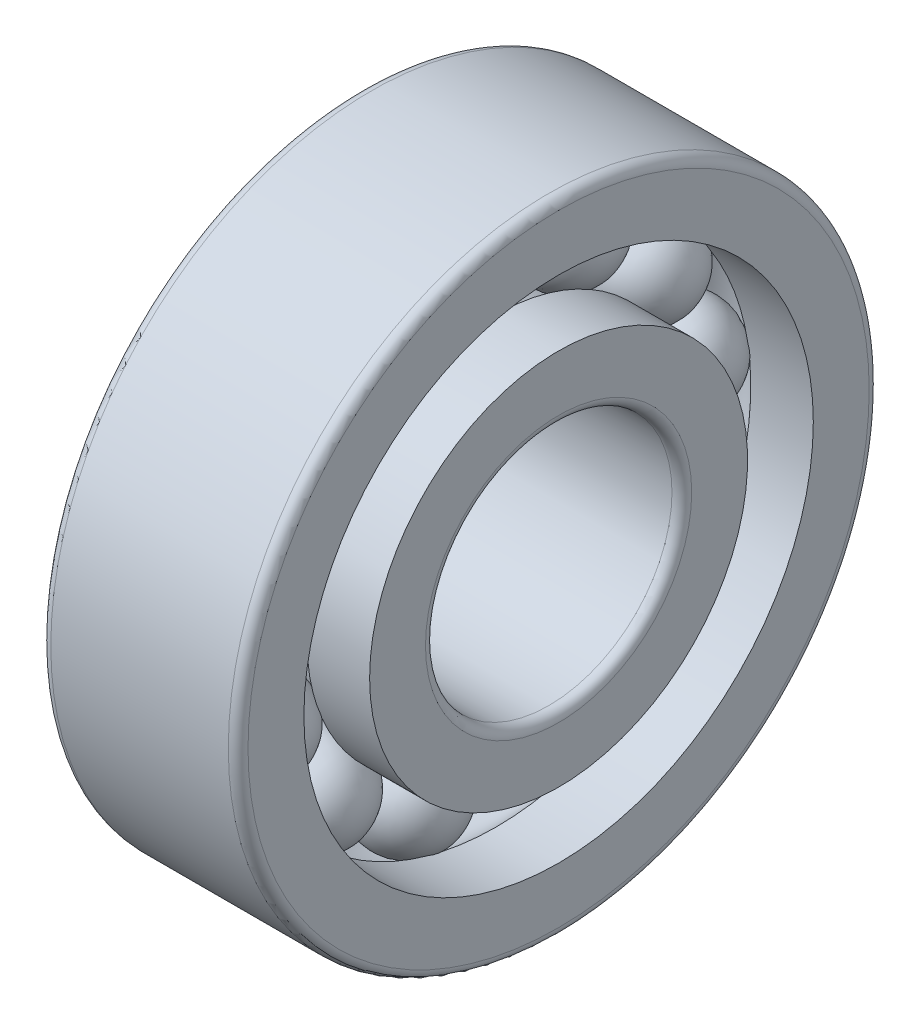
SolidWorks part; units mm, degrees
ref_plane "Front" through (0, 0, 0) normal (0, 0, 1) x (1, 0, 0)
ref_plane "Top" through (0, 0, 0) normal (0, 1, 0) x (1, 0, 0)
ref_plane "Right" through (0, 0, 0) normal (1, 0, 0) x (0, 0, -1)
other "Configuration Table"
sketch "Sketch1" plane through (0, 0, 0) normal (0, 0, 1) x (1, 0, 0)
  line L0 (-9.6833, 0) -> (9.8371, 0) construction
  line L1 (-1, 4.5) -> (1, 4.5)
  line L2 (-4.5966, 4.5) -> (4.6657, 4.5) construction
  arc A0 (1, 4.5) -> (-1, 4.5) centre (0, 4.5) ccw
  dimension "dia" = 2
  dimension "d0" = 9
revolve "Revolve1" add sketch "Sketch1" angle 360 about L2
sketch "Sketch2" plane through (0, 0, 0) normal (0, 0, 1) x (1, 0, 0)
  line L0 (-2, 3.8333) -> (-2, 2.5)
  line L1 (-2, 2.5) -> (2, 2.5)
  line L2 (2, 2.5) -> (2, 3.8333)
  line L3 (2, 3.8333) -> (0.7319, 3.8333)
  line L4 (-6.9714, 0) -> (8.1665, 0) construction
  line L5 (-6.7058, 4.5) -> (6.7058, 4.5) construction
  line L6 (-0.7319, 3.8333) -> (-2, 3.8333)
  arc A0 (-0.7319, 3.8333) -> (0.7319, 3.8333) centre (0, 4.5) ccw
  dimension "B" = 4
  dimension "B/2" = 2
  dimension "D5" = 1.98
  dimension "d" = 5
  dimension "D3" = 4.5
  dimension "D4" = 1.3333
revolve "Revolve2" add sketch "Sketch2" angle 360 about L4
sketch "Sketch3" plane through (0, 0, 0) normal (0, 0, 1) x (1, 0, 0)
  line L0 (-8.7107, 0) -> (9.1288, 0) construction
  line L1 (-2, 6.5) -> (2, 6.5)
  line L2 (-2, 6.5) -> (-2, 5.1667)
  line L3 (-2, 5.1667) -> (-0.7319, 5.1667)
  line L4 (2, 6.5) -> (2, 5.1667)
  line L5 (-7.2948, 4.5) -> (7.2948, 4.5) construction
  line L6 (0.7319, 5.1667) -> (2, 5.1667)
  arc A0 (0.7319, 5.1667) -> (-0.7319, 5.1667) centre (0, 4.5) ccw
  dimension "D1" = 1.98
  dimension "DD" = 13
  dimension "B" = 4
  dimension "D4" = 4.5
  dimension "D5" = 1.3333
  dimension "B/2" = 2
revolve "Revolve3" add sketch "Sketch3" angle 360 about L0
pattern_circular "Circular-Pattern1" count 13 over 360 about axis through (0, 0, 0) along (1, 0, 0) of "Revolve1"
fillet "Fillet1" radius 0.2 4 edges at (-2, 0, 2.5) (-2, 0, 6.5) (2, 0, 6.5) (2, 0, 2.5)
equation "\"d0@Sketch1\" = ( \"DD@Sketch3\" + \"d@Sketch2\" )  / 2"
equation "\"dia@Sketch1\" =  ( \"DD@Sketch3\" - \"d@Sketch2\" )  / 4"
equation "\"D3@Sketch2\" = ( \"DD@Sketch3\" + \"d@Sketch2\" )  / 2 / 2"
equation "\"D4@Sketch2\" = ( \"DD@Sketch3\" - \"d@Sketch2\" )  / 6"
equation "\"D5@Sketch2\" = \"dia@Sketch1\" - 0.02"
equation "\"B/2@Sketch2\" = \"B@Sketch2\" / 2"
equation "\"D4@Sketch3\" = ( \"DD@Sketch3\" + \"d@Sketch2\" )  / 2 / 2"
equation "\"D5@Sketch3\" = ( \"DD@Sketch3\" - \"d@Sketch2\" )  / 6"
equation "\"B@Sketch3\" = \"B@Sketch2\""
equation "\"B/2@Sketch3\" = \"B@Sketch3\" / 2"
equation "\"D1@Sketch3\" = \"dia@Sketch1\" - 0.02"
equation "\"m@Circular-Pattern1\" = int( 3.14159265 / atn(( \"dia@Sketch1\" / 2) / sqr(( \"DD@Sketch3\" + \"d@Sketch2\" )  / 2 * ( \"DD@Sketch3\" + \"d@Sketch2\" )  / 2/4 - ( \"dia@Sketch1\" / 2) *  ( \"dia@Sketch1\" / 2))))-1"
